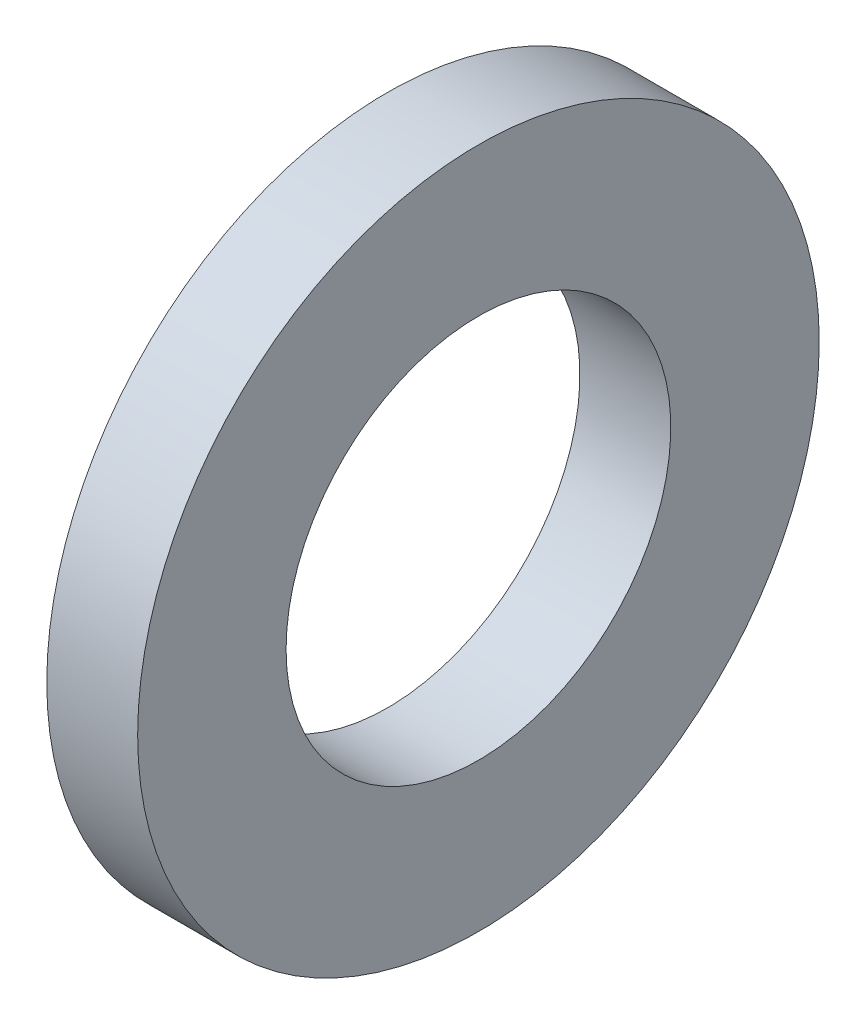
SolidWorks part; units mm, degrees
material "PLA2"
ref_plane "Front Plane" through (0, 0, 0) normal (0, 0, 1) x (1, 0, 0)
ref_plane "Top Plane" through (0, 0, 0) normal (0, 1, 0) x (1, 0, 0)
ref_plane "Right Plane" through (0, 0, 0) normal (1, 0, 0) x (0, 0, -1)
sketch "Sketch1" plane through (0, 0, 0) normal (1, 0, 0) x (0, 0, -1)
  circle A0 centre (0, 0) radius 3.2258
  circle A1 centre (0, 0) radius 5.715
  dimension "D1" = 6.4516
  dimension "D2" = 11.43
extrude "Boss-Extrude1" add sketch "Sketch1" along normal blind 0.762
sketch "Sketch2" plane through (0.762, 0, 0) normal (-1, 0, 0) x (0, 0, 1)
  circle A0 centre (0, 0) radius 5.715
  circle A1 centre (0, 0) radius 3.2258 construction
  circle A2 centre (0, 0) radius 3.2258
  dimension "D1" = 11.43
extrude "Boss-Extrude2" add sketch "Sketch2" against normal blind 0.762
